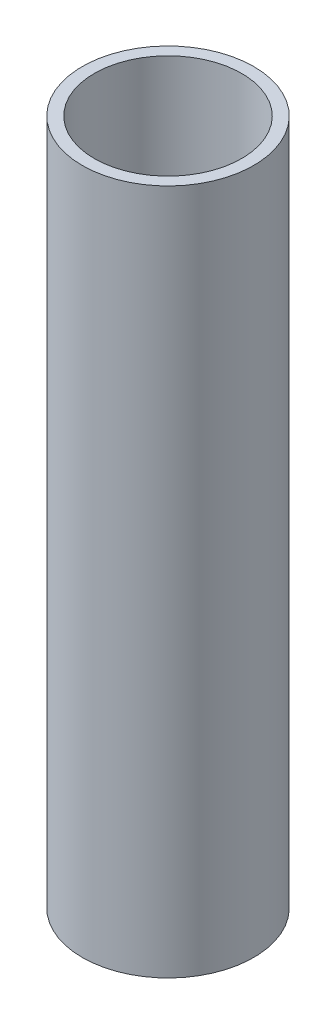
SolidWorks part; units mm, degrees
ref_plane "Ön Düzlem" through (0, 0, 0) normal (0, 0, 1) x (1, 0, 0)
ref_plane "Üst Düzlem" through (0, 0, 0) normal (0, 1, 0) x (1, 0, 0)
ref_plane "Sağ Düzlem" through (0, 0, 0) normal (1, 0, 0) x (0, 0, -1)
sketch "Sketch4" plane through (0, 0, 0) normal (0, 1, 0) x (1, 0, 0)
  circle A0 centre (0, 0) radius 25
  circle A1 centre (0, 0) radius 21.5
  dimension "D1" = 50
  dimension "D2" = 3.5
extrude "Boss-Extrude1" add sketch "Sketch4" along normal blind 200
